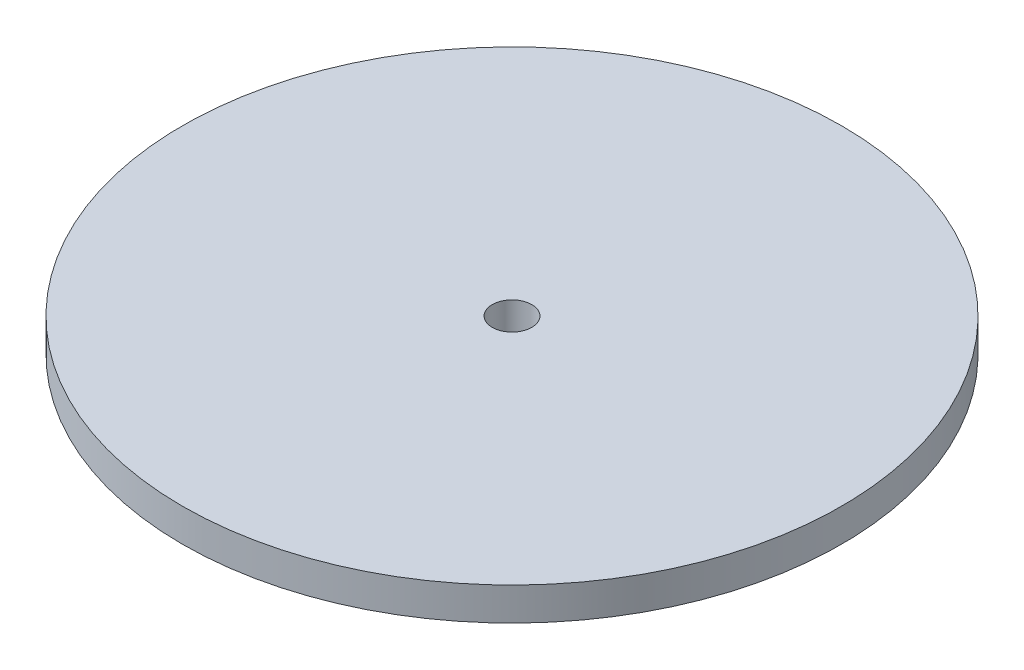
SolidWorks part; units mm, degrees
material "AISI 316 Stainless Steel Sheet (SS)"
ref_plane "Front Plane" through (0, 0, 0) normal (0, 0, 1) x (1, 0, 0)
ref_plane "Top Plane" through (0, 0, 0) normal (0, 1, 0) x (1, 0, 0)
ref_plane "Right Plane" through (0, 0, 0) normal (1, 0, 0) x (0, 0, -1)
sketch "Sketch1" plane through (0, 0, 0) normal (1, 0, 0) x (0, 0, -1)
  line L0 (0, 285.5556) -> (0, 25) construction
  line L1 (-500, 25) -> (-500, -25)
  line L2 (-500, 25) -> (-30, 25)
  line L3 (-500, -25) -> (-30, -25)
  line L4 (0, 25) -> (0, -25) construction
  line L5 (-30, 25) -> (-30, -25)
  line L6 (-30, -25) -> (0, -25) construction
  line L7 (0, 25) -> (0, -25) construction
  line L8 (0, -25) -> (0, -214.4444) construction
  line L9 (-30, 25) -> (0, 25) construction
  point P5 (-500, 0)
  dimension "D1" = 1000
  dimension "D2" = 50
  dimension "D3" = 30
revolve "Revolve1" add sketch "Sketch1" angle 360 about L0
sketch "Sketch2" plane through (0, -25, 0) normal (0, -1, 0) x (1, 0, 0)
  line L0 (0, 0) -> (0, 604.4151) construction
  line L1 (-180, 446.4762) -> (-122.573, 307.8351)
  line L2 (122.573, 307.8351) -> (180, 446.4762)
  line L3 (188.4271, 442.9855) -> (131.0001, 304.3445)
  line L4 (304.3445, 131.0001) -> (442.9855, 188.4271)
  line L5 (446.4762, 180) -> (307.8351, 122.573)
  line L6 (307.8351, -122.573) -> (446.4762, -180)
  line L7 (442.9855, -188.4271) -> (304.3445, -131.0001)
  line L8 (131.0001, -304.3445) -> (188.4271, -442.9855)
  line L9 (180, -446.4762) -> (122.573, -307.8351)
  line L10 (-122.573, -307.8351) -> (-180, -446.4762)
  line L11 (-188.4271, -442.9855) -> (-131.0001, -304.3445)
  line L12 (-304.3445, -131.0001) -> (-442.9855, -188.4271)
  line L13 (-446.4762, -180) -> (-307.8351, -122.573)
  line L14 (-307.8351, 122.573) -> (-446.4762, 180)
  line L15 (-442.9855, 188.4271) -> (-304.3445, 131.0001)
  line L16 (-131.0001, 304.3445) -> (-188.4271, 442.9855)
  arc A1 (-122.573, 307.8351) -> (122.573, 307.8351) centre (0, -20) cw
  arc A2 (180, 446.4762) -> (-180, 446.4762) centre (0, -20) ccw
  arc A3 (442.9855, 188.4271) -> (188.4271, 442.9855) centre (-14.1421, -14.1421) ccw
  arc A4 (131.0001, 304.3445) -> (304.3445, 131.0001) centre (-14.1421, -14.1421) cw
  arc A5 (446.4762, -180) -> (446.4762, 180) centre (-20, 0) ccw
  arc A6 (307.8351, 122.573) -> (307.8351, -122.573) centre (-20, 0) cw
  arc A7 (188.4271, -442.9855) -> (442.9855, -188.4271) centre (-14.1421, 14.1421) ccw
  arc A8 (304.3445, -131.0001) -> (131.0001, -304.3445) centre (-14.1421, 14.1421) cw
  arc A9 (-180, -446.4762) -> (180, -446.4762) centre (0, 20) ccw
  arc A10 (122.573, -307.8351) -> (-122.573, -307.8351) centre (0, 20) cw
  arc A11 (-442.9855, -188.4271) -> (-188.4271, -442.9855) centre (14.1421, 14.1421) ccw
  arc A12 (-131.0001, -304.3445) -> (-304.3445, -131.0001) centre (14.1421, 14.1421) cw
  arc A13 (-446.4762, 180) -> (-446.4762, -180) centre (20, 0) ccw
  arc A14 (-307.8351, -122.573) -> (-307.8351, 122.573) centre (20, 0) cw
  arc A15 (-188.4271, 442.9855) -> (-442.9855, 188.4271) centre (14.1421, -14.1421) ccw
  arc A16 (-304.3445, 131.0001) -> (-131.0001, 304.3445) centre (14.1421, -14.1421) cw
  point P46 (0, 0)
  dimension "D1" = 500
  dimension "D2" = 350
  dimension "D3" = 45
  dimension "D4" = 360
  dimension "D5" = 20
  dimension "D6" = 8
extrude "Cut-Extrude1" cut sketch "Sketch2" against normal blind 20
